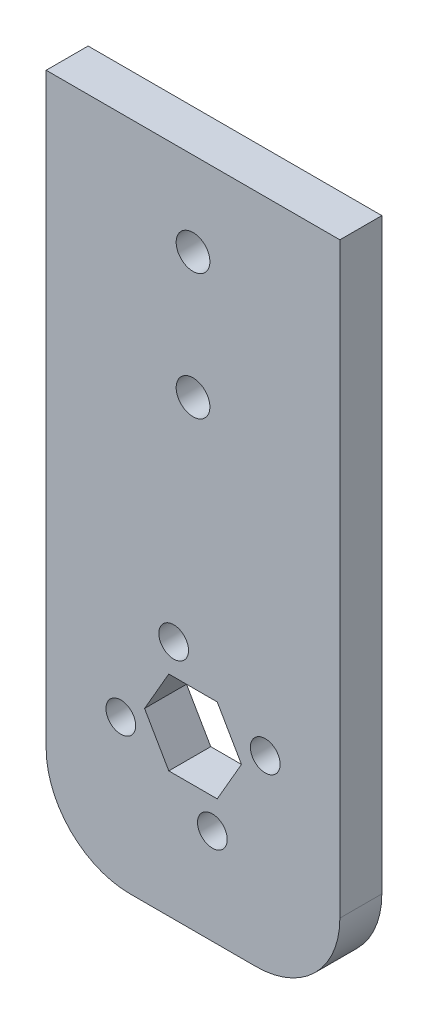
SolidWorks part; units mm, degrees
material "6061 Alloy"
ref_plane "Front Plane" through (0, 0, 0) normal (0, 0, 1) x (1, 0, 0)
ref_plane "Top Plane" through (0, 0, 0) normal (0, 1, 0) x (1, 0, 0)
ref_plane "Right Plane" through (0, 0, 0) normal (1, 0, 0) x (0, 0, -1)
sketch "Sketch1" plane through (0, 0, 0) normal (0, 0, 1) x (1, 0, 0)
  line L1 (0, 0) -> (-44.45, 0)
  line L2 (0, 0) -> (0, 101.6)
  line L3 (0, 101.6) -> (-44.45, 101.6)
  line L4 (-44.45, 0) -> (-44.45, 101.6)
  dimension "D1" = 101.6
  dimension "D2" = 44.45
extrude "Boss-Extrude2" add sketch "Sketch1" along normal blind 6.35
sketch "Sketch3" plane through (0, 0, 0) normal (0, 0, -1) x (-1, 0, 0)
  line L0 (22.225, 101.6) -> (22.225, 0) construction
  line L1 (0, 101.6) -> (44.45, 101.6) construction
  line L2 (44.45, 0) -> (0, 0) construction
  point P3 (22.225, 50.8)
fillet "Fillet1" radius 12.7 2 edges at (-44.45, 0, 3.175) (0, 0, 3.175)
hole_wizard "#7 (0.201) Diameter Hole2" positions "Sketch11" profile "Sketch12" hole size "#7" standard "ANSI Inch" end condition through all
sketch "Sketch11" plane through (0, 0, 0) normal (0, 0, -1) x (-1, 0, 0)
  line L0 (22.225, 101.6) -> (22.225, 0) construction
  line L1 (0, 101.6) -> (44.45, 101.6) construction
  point P0 (22.225, 88.9)
  point P4 (22.225, 69.85)
  dimension "D1" = 19.05
  dimension "D2" = 12.7
sketch "Sketch12" plane through (-22.225, 88.9, 0) normal (1, 0, 0) x (0, 1, 0)
  line L0 (0, 0) -> (0, 6.35)
  line L1 (0, 6.35) -> (2.5527, 6.35)
  line L2 (2.5527, 6.35) -> (2.5527, 0)
  line L5 (2.5527, 0) -> (0, 0)
  line L11 (0, -6.35) -> (0, 107.95) construction
  dimension "Thru Hole Dia." = 5.1054
  dimension "Thru Hole Depth" = 6.35
sketch "Sketch14" plane through (0, 0, 6.35) normal (0, 0, 1) x (1, 0, 0)
  line L0 (-22.225, 101.6) -> (-22.225, 0) construction
  line L1 (-14.8927, 25.4) -> (-18.5588, 31.75)
  line L2 (-18.5588, 31.75) -> (-25.8912, 31.75)
  line L3 (-25.8912, 31.75) -> (-29.5573, 25.4)
  line L4 (-29.5573, 25.4) -> (-25.8912, 19.05)
  line L5 (-25.8912, 19.05) -> (-18.5588, 19.05)
  line L6 (-18.5588, 19.05) -> (-14.8927, 25.4)
  line L7 (-31.75, 0) -> (-12.7, 0) construction
  circle A0 centre (-22.225, 25.4) radius 6.35 construction
  point P12 (-22.225, 31.75)
  dimension "D1" = 12.7
  dimension "D2" = 25.4
extrude "Cut-Extrude1" cut sketch "Sketch14" against normal through all
sketch "Sketch22" plane through (0, 0, 6.35) normal (0, 0, 1) x (1, 0, 0)
  circle A0 centre (-25.1532, 36.3282) radius 2.05
  circle A1 centre (-11.2968, 28.3282) radius 2.05
  circle A2 centre (-19.2968, 14.4718) radius 2.05
  circle A3 centre (-33.1532, 22.4718) radius 2.05
hole_wizard "M4 Clearance Hole1" positions "Sketch25" profile "Sketch24" hole size "M4" standard "ANSI Metric" end condition through all
sketch "Sketch25" plane through (0, 0, 0) normal (0, 0, -1) x (-1, 0, 0)
  point P0 (11.2968, 28.3282)
  point P3 (25.1532, 36.3282)
  point P6 (33.1532, 22.4718)
  point P9 (19.2968, 14.4718)
sketch "Sketch24" plane through (-11.2968, 28.3282, 0) normal (1, 0, 0) x (0, 1, 0)
  line L0 (0, 0) -> (0, 6.35)
  line L1 (0, 6.35) -> (2.25, 6.35)
  line L2 (2.25, 6.35) -> (2.25, 0)
  line L5 (2.25, 0) -> (0, 0)
  line L11 (0, -6.35) -> (0, 107.95) construction
  dimension "Thru Hole Dia." = 4.5
  dimension "Thru Hole Depth" = 6.35
sketch "Sketch26" plane through (0, 0, 0) normal (0, 0, -1) x (-1, 0, 0)
  line L0 (14.8927, 25.4) -> (29.5573, 25.4) construction
  line L1 (18.5588, 19.05) -> (25.8912, 31.75) construction
  circle A0 centre (22.225, 25.4) radius 7.3323
